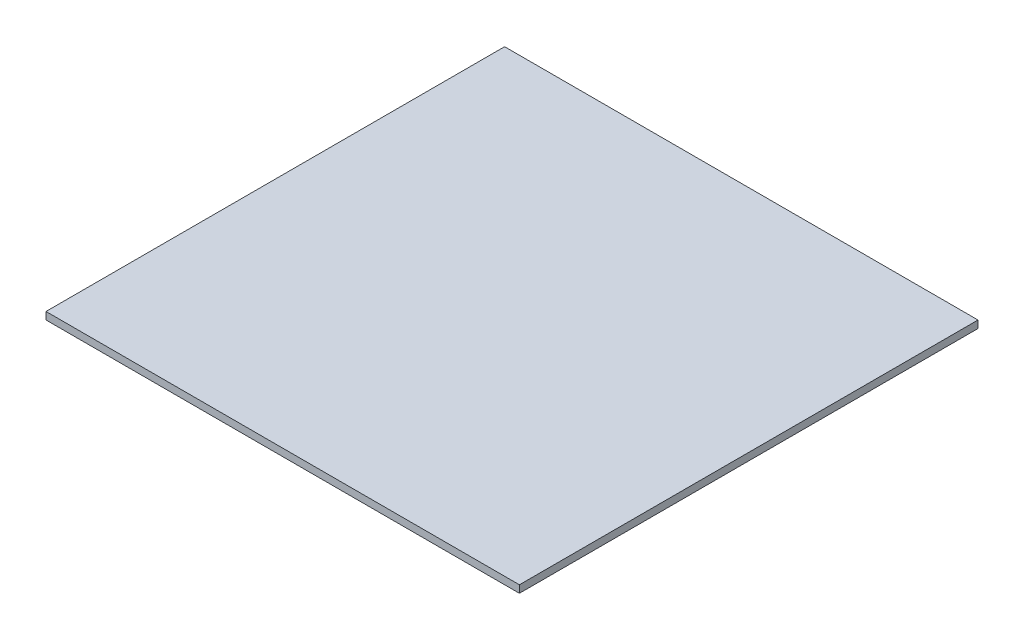
SolidWorks part; units mm, degrees
ref_plane "Front Plane" through (0, 0, 0) normal (0, 0, 1) x (1, 0, 0)
ref_plane "Top Plane" through (0, 0, 0) normal (0, 1, 0) x (1, 0, 0)
ref_plane "Right Plane" through (0, 0, 0) normal (1, 0, 0) x (0, 0, -1)
sketch "Sketch2" plane through (0, 0, 0) normal (0, 1, 0) x (1, 0, 0)
  line L1 (-101.6, -98.425) -> (101.6, -98.425)
  line L2 (-101.6, -98.425) -> (-101.6, 98.425)
  line L3 (-101.6, 98.425) -> (101.6, 98.425)
  line L4 (101.6, -98.425) -> (101.6, 98.425)
  line L5 (-101.6, -98.425) -> (101.6, 98.425) construction
  line L6 (-101.6, 98.425) -> (101.6, -98.425) construction
  point P0 (0, 0)
  dimension "D1" = 203.2
  dimension "D2" = 196.85
extrude "Boss-Extrude1" add sketch "Sketch2" along normal blind 3.175
